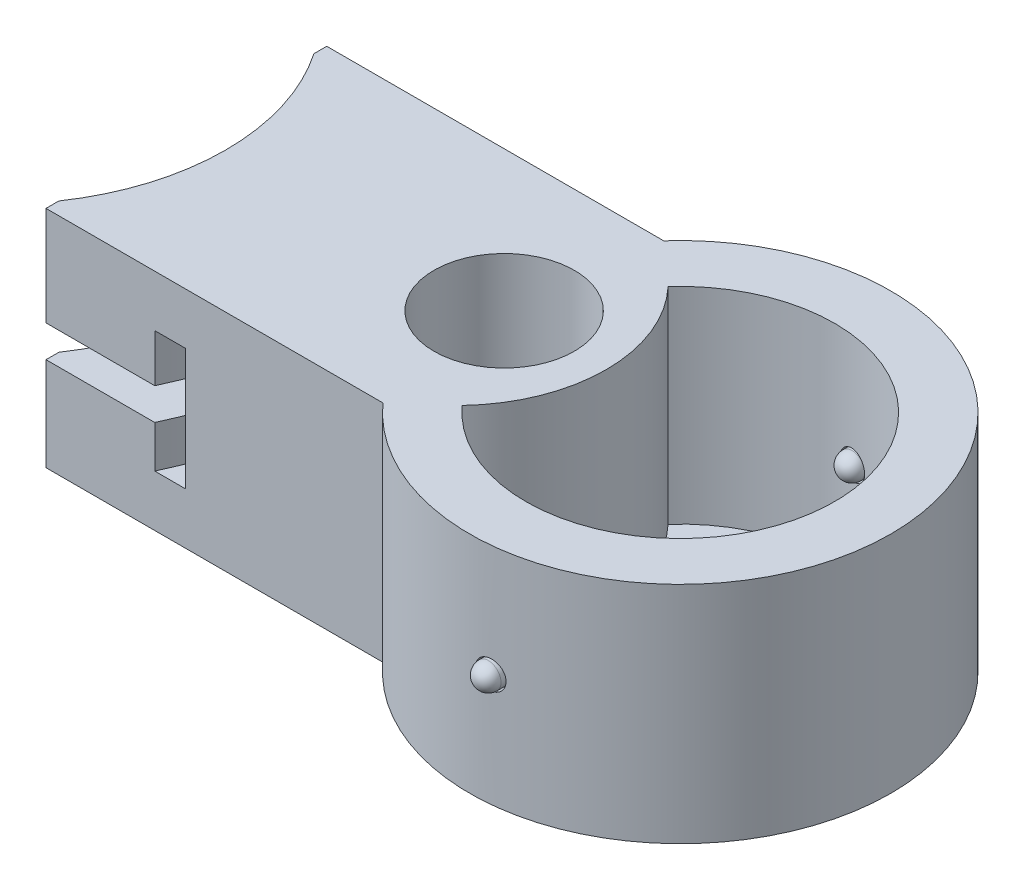
SolidWorks part; units mm, degrees
ref_plane "Front Plane" through (0, 0, 0) normal (0, 0, 1) x (1, 0, 0)
ref_plane "Top Plane" through (0, 0, 0) normal (0, 1, 0) x (1, 0, 0)
ref_plane "Right Plane" through (0, 0, 0) normal (1, 0, 0) x (0, 0, -1)
sketch "Sketch1" plane through (0, 0, 0) normal (0, 1, 0) x (1, 0, 0)
  line L1 (0, 19.05) -> (45.72, 19.05)
  line L2 (0, 19.05) -> (0, -19.05)
  line L3 (0, -19.05) -> (45.72, -19.05)
  arc A0 (45.72, -19.05) -> (45.72, 19.05) centre (67.0185, 0) ccw
  dimension "D2" = 45.72
  dimension "D1" = 57.15
  dimension "D3" = 38.1
extrude "Boss-Extrude1" add sketch "Sketch1" along normal mid plane 30.48 contours L1 A0 L3 L2
sketch "Sketch3" plane through (0, 15.24, 0) normal (0, 1, 0) x (1, 0, 0)
  arc A1 (51.3996, 13.97) -> (51.3996, -13.97) centre (36.6435, 0) cw
  arc A2 (51.3996, -13.97) -> (51.3996, 13.97) centre (67.0185, 0) ccw
  arc A3 (51.3996, -13.97) -> (51.3996, 13.97) centre (67.0185, 0) ccw
  dimension "D2" = 20.32
  dimension "D1" = 7.62
extrude "Cut-Extrude1" cut sketch "Sketch3" against normal blind 27.94 contours A3 A1
sketch "Sketch4" plane through (0, 0, 0) normal (0, 0, 1) x (1, 0, 0)
  line L1 (95.5935, -15.24) -> (95.5935, 15.24) construction
  circle A0 centre (69.6855, 0) radius 1.905
  dimension "D1" = 3.81
  dimension "D2" = 25.908
extrude "Cut-Extrude2" cut sketch "Sketch4" against normal through all both and the other way through all
sketch "Sketch5" plane through (0, 0, 0) normal (0, 1, 0) x (1, 0, 0)
  line L1 (69.6347, -18.9599) -> (69.6347, -30.3899)
  line L2 (71.3619, -28.6627) -> (71.3619, -20.6871)
  arc A0 (69.6347, -30.3899) -> (71.3619, -28.6627) centre (69.6347, -28.6627) ccw
  arc A1 (71.3619, -20.6871) -> (69.6347, -18.9599) centre (69.6347, -20.6871) ccw
  arc A2 (67.7805, -28.5648) -> (71.5905, -28.2069) centre (67.0185, 0) ccw construction
  arc A3 (67.7805, -20.9411) -> (71.5905, -20.4502) centre (67.0185, 0) ccw construction
  arc A4 (67.7805, -28.5648) -> (71.5905, -28.2069) centre (67.0185, 0) ccw
  arc A5 (67.7805, -20.9411) -> (71.5905, -20.4502) centre (67.0185, 0) ccw
  dimension "D2" = 1.7272
  dimension "D1" = 0.2286
  dimension "D3" = 11.43
  dimension "D4" = 0.254
revolve "Revolve1" add sketch "Sketch5" angle 360 about L1
mirror "Mirror1" about plane through (0, 0, 0) normal (0, 0, 1) of bodies 104
sketch "Sketch2" plane through (0, 0, 0) normal (0, 0, 1) x (1, 0, 0)
  line L0 (-3.048, 17.145) -> (5.334, 17.145)
  line L1 (5.334, 17.145) -> (5.334, 1.778)
  line L2 (5.334, 1.778) -> (19.05, 1.778)
  line L3 (19.05, 1.778) -> (19.05, 8.255)
  line L4 (19.05, 8.255) -> (22.86, 8.255)
  line L5 (22.86, 8.255) -> (22.86, -8.255)
  line L6 (22.86, -8.255) -> (19.05, -8.255)
  line L7 (19.05, -8.255) -> (19.05, -2.54)
  line L8 (19.05, -2.54) -> (5.334, -2.54)
  line L9 (5.334, -2.54) -> (5.334, -17.145)
  line L10 (5.334, -17.145) -> (-3.048, -17.145)
  line L11 (-3.048, -17.145) -> (-3.048, 17.145)
  line L12 (0, 15.24) -> (0, -15.24) construction
  point P2 (22.86, 0)
  point P13 (-3.048, 0)
  dimension "D1" = 3.048
  dimension "D2" = 8.382
  dimension "D3" = 8.382
  dimension "D4" = 34.29
  dimension "D5" = 4.318
  dimension "D6" = 1.778
  dimension "D7" = 13.716
  dimension "D8" = 3.81
  dimension "D9" = 16.51
ref_plane "Plane1" through (-25.4, 0, 0) normal (1, 0, 0) x (0, 0, -1)
ref_axis "Axis1" through (-25.4, 18.8595, 0) along (0, -1, 0)
revolve "Cut-Revolve1" cut sketch "Sketch2" angle 360 about axis through (-25.4, 18.8595, 0) along (0, -1, 0)
ref_point "Point1"
sketch "Sketch6" plane through (0, 15.24, 0) normal (0, 1, 0) x (1, 0, 0)
  circle A0 centre (43.1193, 0) radius 9.525
  dimension "D1" = 19.05
extrude "Cut-Extrude3" cut sketch "Sketch6" against normal through all contours A0
